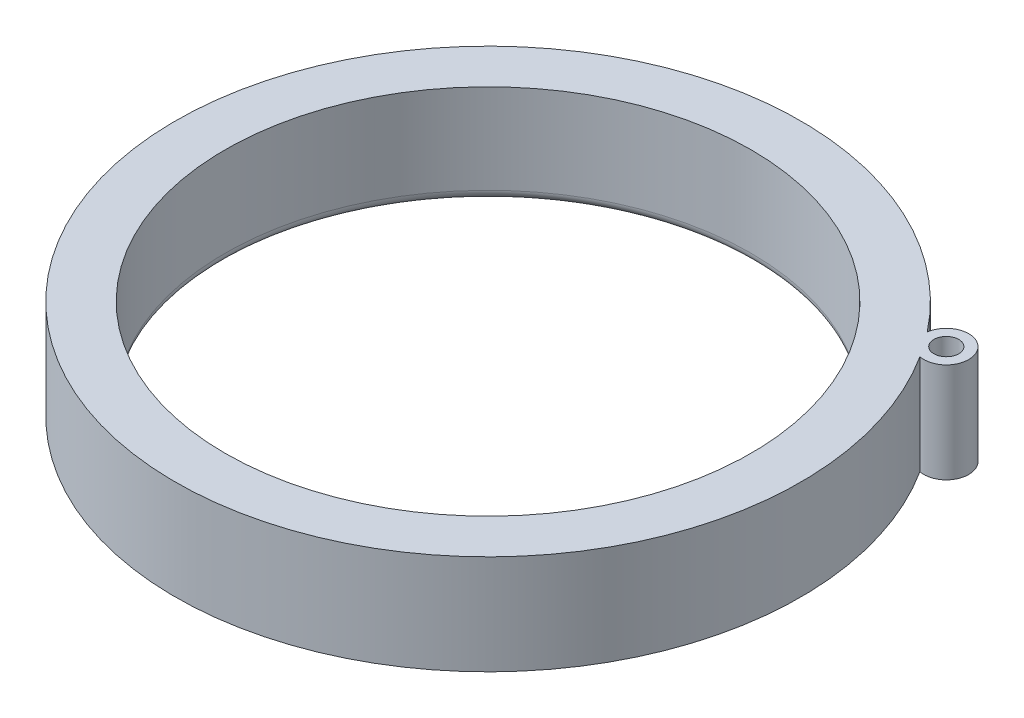
SolidWorks part; units mm, degrees
ref_plane "前视基准面" through (0, 0, 0) normal (0, 0, 1) x (1, 0, 0)
ref_plane "上视基准面" through (0, 0, 0) normal (0, 1, 0) x (1, 0, 0)
ref_plane "右视基准面" through (0, 0, 0) normal (1, 0, 0) x (0, 0, -1)
other "Configuration Table"
sketch "草图1" plane through (0, 0, 0) normal (0, 1, 0) x (1, 0, 0)
  circle A0 centre (0, 0) radius 26.4
  arc A1 (24.6965, 19.3918) -> (26.4804, 16.8746) centre (0, 0) ccw
  circle A2 centre (26.9248, 19.0802) radius 1.25
  arc A3 (26.4804, 16.8746) -> (24.6965, 19.3918) centre (26.9248, 19.0802) ccw
  circle A4 centre (0, 0) radius 31.4 construction
  circle A5 centre (26.9248, 19.0802) radius 2.25 construction
  dimension "D1" = 52.8
  dimension "D3" = 2.5
  dimension "D4" = 33
  dimension "D2" = 5
  dimension "D5" = 1
extrude "凸台-拉伸1" add sketch "草图1" along normal blind 10
fillet "圆角1" radius 1 1 edges at (0, 0, 26.4)
